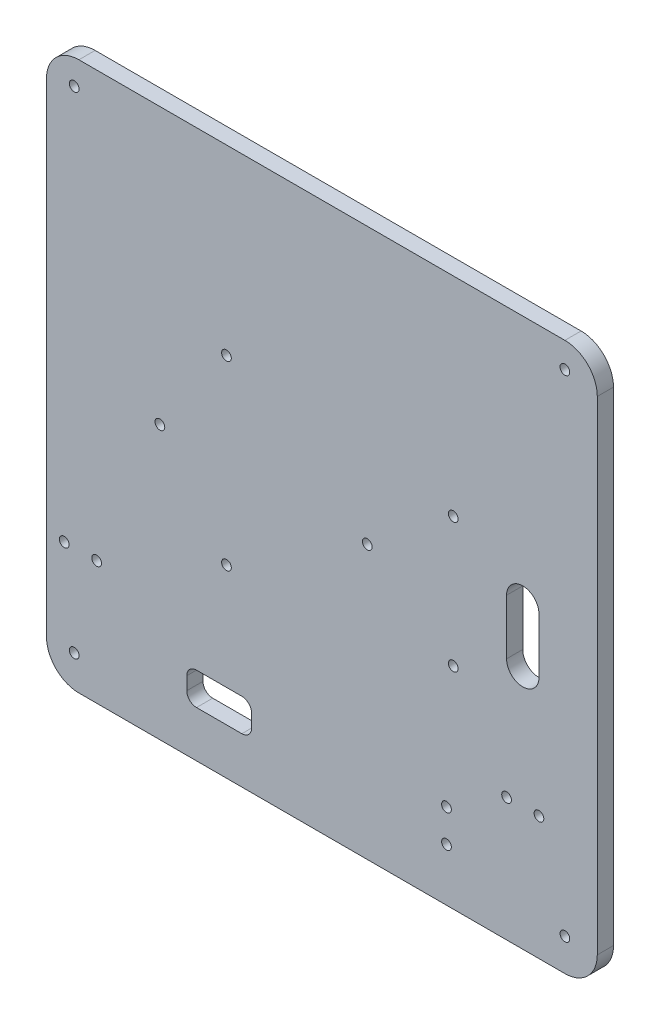
SolidWorks part; units mm, degrees
ref_plane "Front Plane" through (0, 0, 0) normal (0, 0, 1) x (1, 0, 0)
ref_plane "Top Plane" through (0, 0, 0) normal (0, 1, 0) x (1, 0, 0)
ref_plane "Right Plane" through (0, 0, 0) normal (1, 0, 0) x (0, 0, -1)
sketch "Sketch1" plane through (0, 0, 0) normal (0, 0, 1) x (1, 0, 0)
  line L0 (56.9978, -46.1452) -> (66.9978, -46.1452) construction
  line L13 (61.9978, 7.8708) -> (61.9978, -9.1292) construction
  line L14 (-38.7038, -60) -> (-24.7038, -60)
  line L15 (-41.7038, -63) -> (-41.7038, -67)
  line L16 (-38.7038, -70) -> (-24.7038, -70)
  line L17 (-21.7038, -63) -> (-21.7038, -67)
  line L18 (66.9978, 7.8708) -> (66.9978, -9.1292)
  line L19 (56.9978, 7.8708) -> (56.9978, -9.1292)
  line L20 (-79.5334, -46.1452) -> (-69.5334, -46.1452) construction
  line L21 (38.4521, -68) -> (38.4521, -58) construction
  line L25 (-75, -84.27) -> (75, -84.27)
  line L26 (-85, -74.27) -> (-85, 75)
  line L27 (-75, 85) -> (75, 85)
  line L28 (85, -74.27) -> (85, 75)
  circle A9 centre (-50, 0) radius 1.5
  circle A11 centre (14, 0) radius 1.5
  arc A14 (-24.7038, -70) -> (-21.7038, -67) centre (-24.7038, -67) ccw
  arc A15 (-24.7038, -60) -> (-21.7038, -63) centre (-24.7038, -63) cw
  arc A16 (-38.7038, -60) -> (-41.7038, -63) centre (-38.7038, -63) ccw
  arc A17 (-41.7038, -67) -> (-38.7038, -70) centre (-38.7038, -67) ccw
  arc A18 (66.9978, 7.8708) -> (56.9978, 7.8708) centre (61.9978, 7.8708) ccw
  arc A19 (56.9978, -9.1292) -> (66.9978, -9.1292) centre (61.9978, -9.1292) ccw
  circle A20 centre (56.9978, -46.1452) radius 1.5
  circle A21 centre (66.9978, -46.1452) radius 1.5
  circle A22 centre (-79.5334, -46.1452) radius 1.5
  circle A23 centre (-69.5334, -46.1452) radius 1.5
  circle A24 centre (38.4521, -68) radius 1.5
  circle A25 centre (38.4521, -58) radius 1.5
  arc A27 (-75, -84.27) -> (-85, -74.27) centre (-75, -74.27) cw
  circle A31 centre (75, -74.2718) radius 1.5
  arc A35 (75, -84.27) -> (85, -74.27) centre (75, -74.27) ccw
  circle A37 centre (-76.4564, -74.2718) radius 1.5
  arc A39 (75, 85) -> (85, 75) centre (75, 75) cw
  circle A40 centre (-76.4564, 77.1847) radius 1.5
  arc A41 (-85, 75) -> (-75, 85) centre (-75, 75) cw
  circle A42 centre (75, 77.1847) radius 1.5
  circle A55 centre (40.5413, 20.7331) radius 1.5
  circle A57 centre (-29.4532, -27.275) radius 1.5
  arc A58 (40.5411, 22.2331) -> (40.5414, 19.2331) centre (40.5413, 20.7331) ccw
  circle A59 centre (40.5459, -19.2669) radius 1.5
  circle A60 centre (-29.4597, 28.725) radius 1.5
  point P45 (-21.7038, -70)
  point P49 (-21.7038, -60)
  point P55 (-41.7038, -70)
  point P58 (61.9978, -0.6292)
  dimension "D3" = 85
  dimension "D4" = 84.27
  dimension "D5" = 74.2718
  dimension "D6" = 10
  dimension "D8" = 9.9982
  dimension "D9" = 10
  dimension "D10" = 3
  dimension "D11" = 3
  dimension "D13" = 3
  dimension "D1" = 85
  dimension "D2" = 85
  dimension "D7" = 9.9982
  dimension "D12" = 3
  dimension "D14" = 3
  dimension "D15" = 3
  dimension "D16" = 3
  dimension "D17" = 3
  dimension "D18" = 3
  dimension "D19" = 3
  dimension "D20" = 3
  dimension "D29" = 3
  dimension "D32" = 24.4521
  dimension "D21" = 3
  dimension "D22" = 3
  dimension "D23" = 3
  dimension "D24" = 3
  dimension "D25" = 3
  dimension "D26" = 3
  dimension "D45" = 0.6292
  dimension "D27" = 3
  dimension "D28" = 3
  dimension "D30" = 5
  dimension "D31" = 14
  dimension "D37" = 8.2962
  dimension "D38" = 19.5334
  dimension "D39" = 6.923
  dimension "D40" = 3.077
  dimension "D41" = 7.8708
  dimension "D49" = 11.8548
  dimension "D50" = 2
  dimension "D51" = 8
other "AlignGroup1"
other "AlignGroup2"
extrude "Boss-Extrude1" add sketch "Sketch1" along normal blind 5
